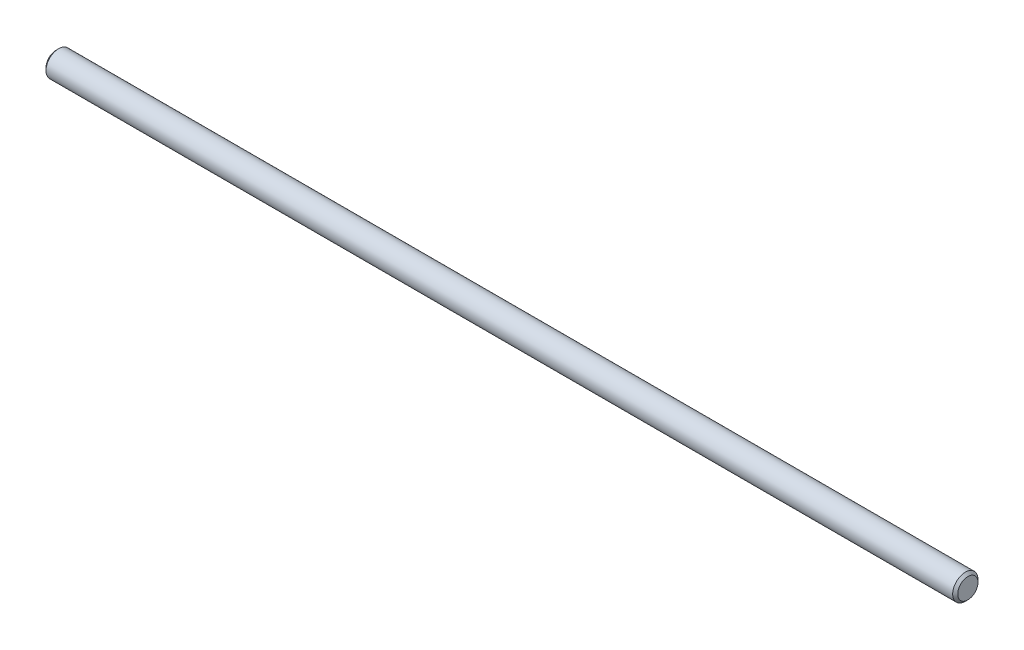
SolidWorks part; units mm, degrees
ref_plane "Front" through (0, 0, 0) normal (0, 0, 1) x (1, 0, 0)
ref_plane "Top" through (0, 0, 0) normal (0, 1, 0) x (1, 0, 0)
ref_plane "Right" through (0, 0, 0) normal (1, 0, 0) x (0, 0, -1)
sketch "Sketch1" plane through (0, 0, 0) normal (0, 0, 1) x (1, 0, 0)
  line L0 (-114.3, 0) -> (114.3, 0) construction
  line L1 (114.3, 3.175) -> (114.3, -3.175) construction
  line L2 (-114.3, 3.175) -> (-114.3, -3.175) construction
  dimension "Length" = 228.6
  dimension "Diameter" = 6.35
sketch "Sketch2" plane through (0, 0, 0) normal (1, 0, 0) x (0, 0, -1)
  circle A0 centre (0, 0) radius 3.175
extrude "Extrude1" add sketch "Sketch2" against normal up to vertex (114.3 mm away) and the other way up to vertex (114.3 mm away) up to point (-114.3, 3.175, 0) other way up to point (114.3, 3.175, 0)
chamfer "Chamfer1" distance 0.635 angle 45 2 edges at (114.3, 0, -3.175) (-114.3, 0, -3.175)
equation "\"D1@Chamfer1\" = \"Diameter@Sketch1\"*.1"
